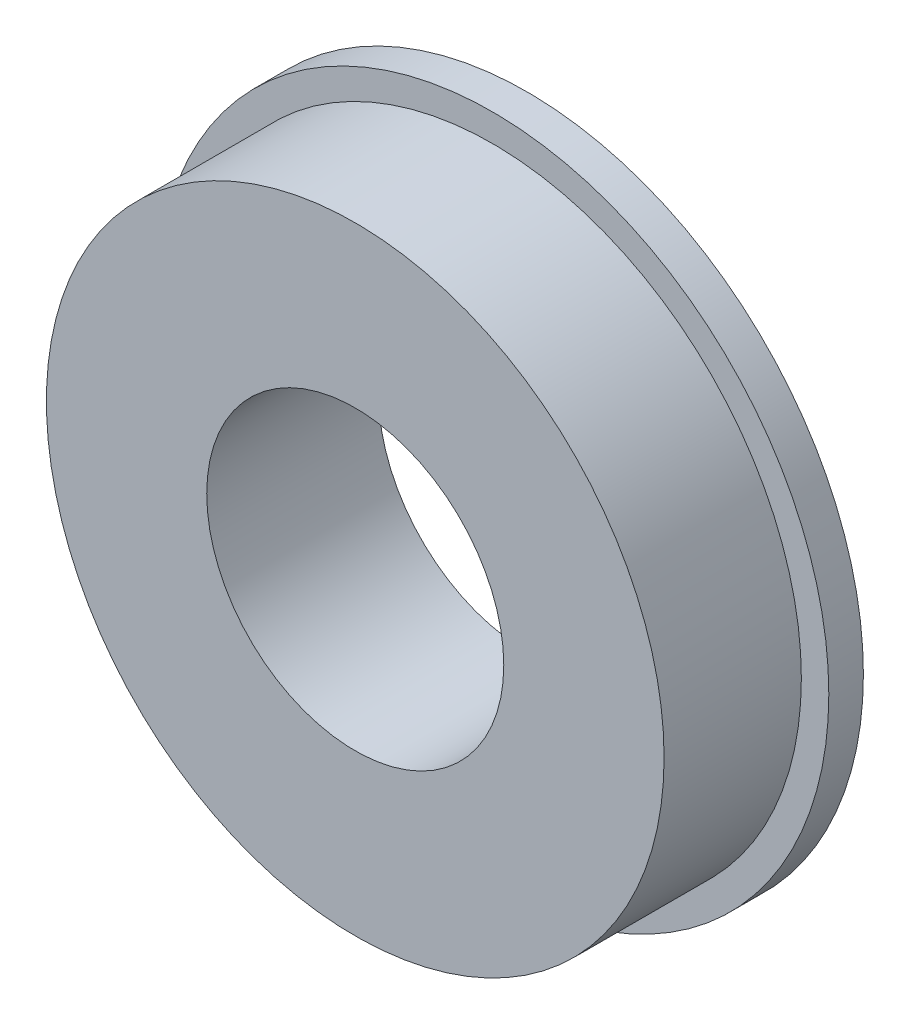
SolidWorks part; units mm, degrees
ref_plane "Front Plane" through (0, 0, 0) normal (0, 0, 1) x (1, 0, 0)
ref_plane "Top Plane" through (0, 0, 0) normal (0, 1, 0) x (1, 0, 0)
ref_plane "Right Plane" through (0, 0, 0) normal (1, 0, 0) x (0, 0, -1)
sketch "Sketch1" plane through (0, 0, 0) normal (0, 1, 0) x (1, 0, 0)
  line L0 (0, 0) -> (2.8956, 0)
  line L1 (2.8956, 0) -> (2.8956, -0.635)
  line L2 (2.8956, -0.635) -> (5.7912, -0.635)
  line L3 (5.7912, -0.635) -> (5.7912, 0)
  line L4 (5.7912, 0) -> (8.6868, 0)
  line L5 (8.6868, 0) -> (8.6868, -7.9502)
  line L6 (8.6868, -7.9502) -> (1.27, -7.9502)
  line L7 (1.27, -7.9502) -> (1.27, -1.6002)
  line L8 (1.27, -1.6002) -> (0, -1.6002)
  line L9 (0, -1.6002) -> (0, 0)
  line L10 (15.5575, -1003.1237) -> (15.5575, 48996.8763) construction
  dimension "D1" = 2.8956
  dimension "D2" = 2.8956
  dimension "D3" = 1.6002
  dimension "D4" = 1.27
  dimension "D5" = 7.4168
  dimension "D6" = 7.9502
  dimension "D7" = 0.635
  dimension "D8" = 6.8707
revolve "Revolve1" add sketch "Sketch1" angle 360 about L10
